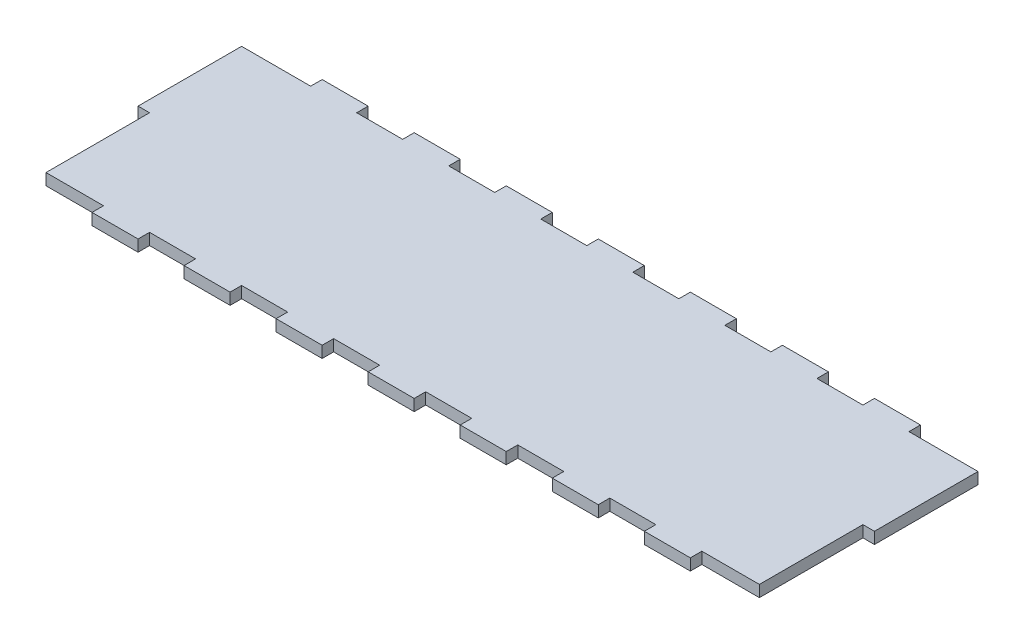
SolidWorks part; units mm, degrees
material "Oak"
ref_plane "Front Plane" through (0, 0, 0) normal (0, 0, 1) x (1, 0, 0)
ref_plane "Top Plane" through (0, 0, 0) normal (0, 1, 0) x (1, 0, 0)
ref_plane "Right Plane" through (0, 0, 0) normal (1, 0, 0) x (0, 0, -1)
sketch "Sketch1" plane through (0, 0, 0) normal (0, 1, 0) x (1, 0, 0)
  line L1 (80, 25) -> (-80, 25)
  line L2 (80, 25) -> (80, -25)
  line L3 (80, -25) -> (-80, -25)
  line L4 (-80, 25) -> (-80, -25)
  line L5 (80, 25) -> (-80, -25) construction
  line L6 (80, -25) -> (-80, 25) construction
  point P0 (0, 0)
  dimension "D1" = 50
  dimension "D2" = 160
extrude "Boss-Extrude1" add sketch "Sketch1" along normal mid plane 2.5
sketch "Sketch2" plane through (0, 1.25, 0) normal (0, 1, 0) x (1, 0, 0)
  line L0 (5, -22.5) -> (-5, -22.5) construction
  line L5 (80, 25) -> (-80, 25) construction
  line L6 (5, 25) -> (-5, 25) construction
  line L11 (5, -22.5) -> (5, -25) construction
  line L24 (5, -25) -> (-5, -25) construction
  line L85 (5, 25) -> (5, 22.5) construction
  line L86 (5, 22.5) -> (-5, 22.5) construction
  line L87 (-5, 25) -> (-5, 22.5) construction
  line L88 (80, -25) -> (80, 25) construction
  line L89 (-5, -22.5) -> (-5, -25) construction
  line L90 (-80, -25) -> (80, -25) construction
  line L115 (25, 22.5) -> (25, 25)
  line L140 (5, 22.5) -> (15, 22.5)
  line L141 (5, 22.5) -> (5, 25)
  line L142 (5, 25) -> (15, 25)
  line L143 (15, 22.5) -> (15, 25)
  line L144 (5, -22.5) -> (15, -22.5)
  line L145 (5, -22.5) -> (5, -25)
  line L146 (5, -25) -> (15, -25)
  line L147 (15, -22.5) -> (15, -25)
  line L148 (25, 22.5) -> (35, 22.5)
  line L149 (35, 22.5) -> (35, 25)
  line L150 (25, 25) -> (35, 25)
  line L151 (25, -22.5) -> (25, -25)
  line L152 (25, -22.5) -> (35, -22.5)
  line L153 (35, -22.5) -> (35, -25)
  line L154 (25, -25) -> (35, -25)
  line L155 (45, 22.5) -> (45, 25)
  line L156 (45, 22.5) -> (55, 22.5)
  line L157 (55, 22.5) -> (55, 25)
  line L158 (45, 25) -> (55, 25)
  line L159 (45, -22.5) -> (45, -25)
  line L160 (45, -22.5) -> (55, -22.5)
  line L161 (55, -22.5) -> (55, -25)
  line L162 (45, -25) -> (55, -25)
  line L163 (5, 22.5) -> (25, 22.5) construction
  line L164 (-15, 22.5) -> (-15, 25)
  line L165 (-15, 22.5) -> (-5, 22.5)
  line L166 (-5, 22.5) -> (-5, 25)
  line L167 (-15, 25) -> (-5, 25)
  line L168 (-15, -22.5) -> (-15, -25)
  line L169 (-15, -22.5) -> (-5, -22.5)
  line L170 (-5, -22.5) -> (-5, -25)
  line L171 (-15, -25) -> (-5, -25)
  line L172 (-35, 22.5) -> (-35, 25)
  line L173 (-35, 22.5) -> (-25, 22.5)
  line L174 (-25, 22.5) -> (-25, 25)
  line L175 (-35, 25) -> (-25, 25)
  line L176 (-35, -22.5) -> (-35, -25)
  line L177 (-35, -22.5) -> (-25, -22.5)
  line L178 (-25, -22.5) -> (-25, -25)
  line L179 (-35, -25) -> (-25, -25)
  line L180 (-55, 22.5) -> (-55, 25)
  line L181 (-55, 22.5) -> (-45, 22.5)
  line L182 (-45, 22.5) -> (-45, 25)
  line L183 (-55, 25) -> (-45, 25)
  line L184 (-55, -22.5) -> (-55, -25)
  line L185 (-55, -22.5) -> (-45, -22.5)
  line L186 (-45, -22.5) -> (-45, -25)
  line L187 (-55, -25) -> (-45, -25)
  line L188 (5, 22.5) -> (-15, 22.5) construction
  line L190 (80, 25) -> (65, 25)
  line L191 (80, 25) -> (80, 22.5)
  line L192 (80, 22.5) -> (65, 22.5)
  line L193 (65, 25) -> (65, 22.5)
  line L194 (80, -25) -> (65, -25)
  line L195 (80, -25) -> (80, -22.5)
  line L196 (80, -22.5) -> (65, -22.5)
  line L197 (65, -25) -> (65, -22.5)
  line L198 (-80, 25) -> (-65, 25)
  line L199 (-80, 25) -> (-80, 22.5)
  line L200 (-80, 22.5) -> (-65, 22.5)
  line L201 (-65, 25) -> (-65, 22.5)
  line L202 (-80, -25) -> (-65, -25)
  line L203 (-80, -25) -> (-80, -22.5)
  line L204 (-80, -22.5) -> (-65, -22.5)
  line L205 (-65, -25) -> (-65, -22.5)
  dimension "D2" = 2.5
  dimension "D1" = 10
  dimension "D3" = 75
  dimension "D4" = 10
  dimension "D5" = 2.5
  dimension "D6" = 75
  dimension "D7" = 10
  dimension "D8" = 10
  dimension "D10" = 20
  dimension "D12" = 20
  dimension "D13" = 2.5
  dimension "D14" = 2.5
  dimension "D15" = 2.5
  dimension "D16" = 2.5
  dimension "D17" = 10
  dimension "D18" = 10
  dimension "D19" = 10
  dimension "D20" = 10
  dimension "D9" = 3
  dimension "D11" = 4
extrude "Cut-Extrude1" cut sketch "Sketch2" against normal blind 4
sketch "Sketch3" plane through (0, 1.25, 0) normal (0, 1, 0) x (1, 0, 0)
  line L0 (0, 0) -> (0, 25) construction
  line L1 (80, 0) -> (77.5, 0)
  line L2 (80, 0) -> (80, -22.5)
  line L3 (80, -22.5) -> (77.5, -22.5)
  line L4 (77.5, 0) -> (77.5, -22.5)
  line L5 (80, -22.5) -> (80, 22.5) construction
  line L6 (5, 25) -> (-5, 25) construction
  line L14 (80, -22.5) -> (65, -22.5) construction
  line L15 (-77.5, 0) -> (-77.5, -22.5)
  line L16 (-80, -22.5) -> (-77.5, -22.5)
  line L17 (-80, 0) -> (-80, -22.5)
  line L18 (-80, 0) -> (-77.5, 0)
  point P5 (78.75, -22.5)
  dimension "D2" = 2.5
  dimension "D3" = 22.5
extrude "Cut-Extrude2" cut sketch "Sketch3" against normal through all
equation "\"thick\"= 0.25"
equation "\"D2@Sketch3\"=\"thick\""
equation "\"corner\"=2.1"
equation "\"D3@Sketch3\"=( +\"width\" - \"thick\" * 2 ) / 2"
equation "\"D1@Boss-Extrude1\"=\"thick\""
equation "\"length\"= 16"
equation "\"width\"=5"
equation "\"D1@Sketch1\"=\"width\""
equation "\"D2@Sketch1\"=\"length\""
equation "\"hole_length\"=1"
equation "\"D1@Sketch2\"=\"hole_length\""
equation "\"D6@Sketch2\"=\"D3@Sketch2\""
equation "\"D5@Sketch2\"=\"thick\""
equation "\"D4@Sketch2\"=\"hole_length\""
equation "\"D3@Sketch2\"=(\"length\" - 1) / 2"
equation "\"D2@Sketch2\"=\"thick\""
equation "\"D7@Sketch2\"=\"D1@Sketch2\""
equation "\"D8@Sketch2\"=\"D1@Sketch2\""
equation "\"D13@Sketch2\"=\"thick\""
equation "\"D14@Sketch2\"=\"D13@Sketch2\""
equation "\"D15@Sketch2\"=\"D13@Sketch2\""
equation "\"D16@Sketch2\"=\"D15@Sketch2\""
equation "\"D17@Sketch2\"=\"hole_length\""
equation "\"D18@Sketch2\"=\"D17@Sketch2\""
equation "\"D19@Sketch2\"=\"D18@Sketch2\""
equation "\"D20@Sketch2\"=\"D19@Sketch2\""
